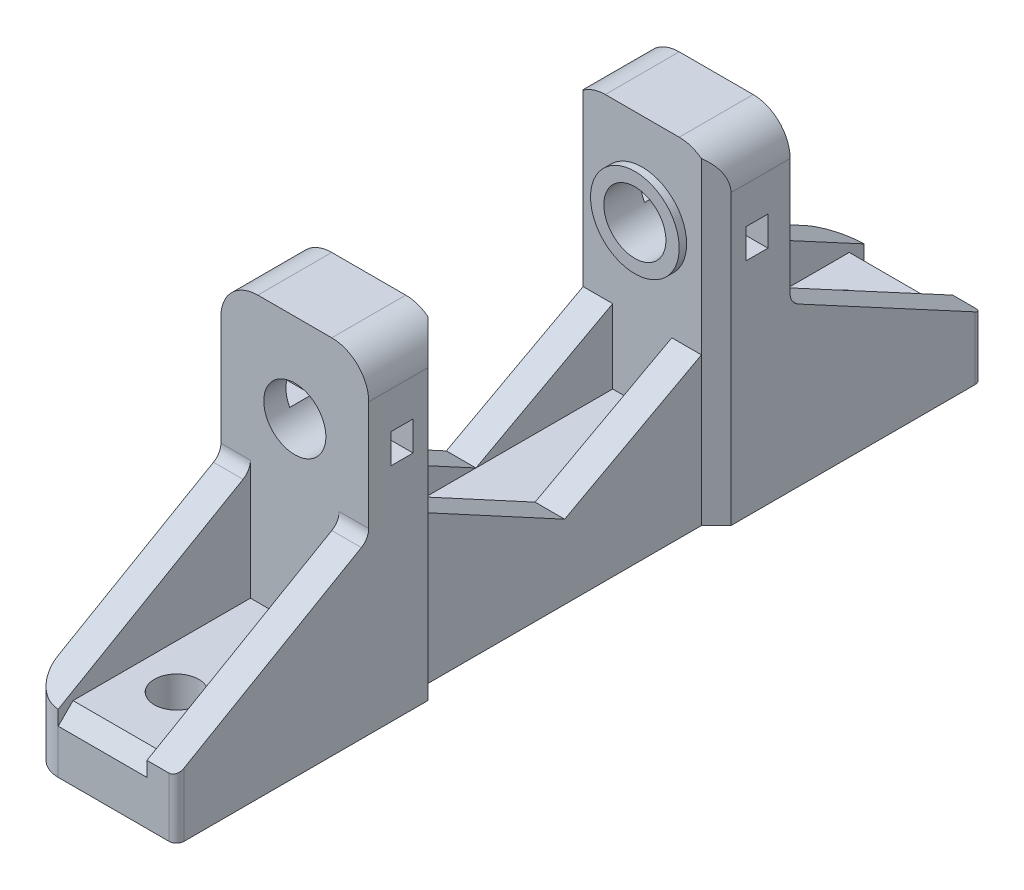
SolidWorks part; units mm, degrees
ref_plane "Спереди" through (0, 0, 0) normal (0, 0, 1) x (1, 0, 0)
ref_plane "Сверху" through (0, 0, 0) normal (0, 1, 0) x (1, 0, 0)
ref_plane "Справа" through (0, 0, 0) normal (1, 0, 0) x (0, 0, -1)
sketch "Эскиз1" plane through (0, 0, 0) normal (0, 0, 1) x (1, 0, 0)
  line L0 (-10, 0) -> (10, 0)
  line L2 (-10, 0) -> (-10, 44)
  line L3 (-10, 44) -> (10, 44)
  line L4 (10, 44) -> (10, 0)
  circle A0 centre (0, 32) radius 4.2
extrude "Бобышка-Вытянуть1" add sketch "Эскиз1" along normal blind 7
ref_plane "Плоскость1" through (0, 0, 7) normal (0, 0, 1) x (1, 0, 0)
sketch "Эскиз2" plane through (0, 0, 7) normal (0, 0, 1) x (1, 0, 0)
  line L0 (-10, 44) -> (10, 44)
  line L1 (10, 44) -> (10, 0)
  line L2 (10, 0) -> (-10, 0)
  line L3 (-10, 0) -> (-10, 44)
extrude "Бобышка-Вытянуть2" add sketch "Эскиз2" along normal blind 3
sketch "Эскиз3" plane through (0, 0, 0) normal (0, 1, 0) x (1, 0, 0)
  line L0 (-10, -10) -> (-10, -36)
  line L1 (-10, -36) -> (10, -36)
  line L2 (10, -36) -> (10, -10)
  line L3 (-10, -10) -> (10, -10)
  circle A0 centre (0, -26) radius 3
  point P6 (0, 0)
  point P7 (0, 0)
  point P8 (0, 0)
  point P11 (0, 0)
extrude "Бобышка-Вытянуть4" add sketch "Эскиз3" along normal blind 8
ref_plane "Плоскость2" through (-10, 0, 0) normal (-1, 0, 0) x (0, 0, 1)
sketch "Эскиз4" plane through (-10, 0, 0) normal (-1, 0, 0) x (0, 0, 1)
  line L0 (36, 8) -> (10, 8)
  line L1 (10, 8) -> (10, 23)
  line L2 (10, 44) -> (10, 8) construction
  line L3 (10, 23) -> (36, 8)
extrude "Бобышка-Вытянуть5" add sketch "Эскиз4" against normal blind 4
ref_plane "Плоскость3" through (10, 0, 0) normal (1, 0, 0) x (0, 0, -1)
sketch "Эскиз5" plane through (10, 0, 0) normal (1, 0, 0) x (0, 0, -1)
  line L0 (-36, 8) -> (-10, 23)
  line L1 (-10, 8) -> (-10, 44) construction
  line L2 (-36, 8) -> (-10, 23) construction
  line L3 (-10, 23) -> (-10, 8)
  line L4 (-10, 8) -> (-36, 8)
extrude "Бобышка-Вытянуть6" add sketch "Эскиз5" against normal blind 4
chamfer "Фаска1" distance 2 angle 45 2 edges at (10, 22, 0) (-10, 22, 0)
fillet "Скругление2" radius 5 2 edges at (-10, 44, 6) (10, 44, 6)
fillet "Скругление3" radius 1 1 edges at (10, 4, 36)
fillet "Скругление4" radius 2 2 edges at (8, 23, 10) (-8, 23, 10)
sketch "Эскиз6" plane through (0, 0, 0) normal (0, 1, 0) x (1, 0, 0)
  line L2 (8, 37) -> (-8, 37)
  line L3 (-8, 37) -> (-8, 0)
  line L4 (8, 37) -> (8, 0)
  line L5 (5, 0) -> (-5, 0) construction
  line L6 (8, 0) -> (-8, 0)
  point P0 (0, 0)
extrude "Бобышка-Вытянуть7" add sketch "Эскиз6" along normal blind 10
ref_plane "Плоскость4" through (0, 0, -37) normal (0, 0, -1) x (-1, 0, 0)
sketch "Эскиз7" plane through (0, 0, -37) normal (0, 0, -1) x (-1, 0, 0)
  line L0 (0, 0) -> (-10, 0)
  line L1 (-10, 21.45) -> (-10, -21.45) construction
  line L2 (-8, 0) -> (-10, 0) construction
  line L3 (-10, 0) -> (-10, 44)
  line L4 (-10, 44) -> (10, 44)
  line L5 (10, 44) -> (10, 0)
  line L6 (10, -21.45) -> (10, 21.45) construction
  line L7 (10, 0) -> (0, 0)
  circle A0 centre (0, 32) radius 4.2
extrude "Бобышка-Вытянуть8" add sketch "Эскиз7" along normal blind 7
chamfer "Фаска2" distance 2 angle 45 2 edges at (10, 22, -37) (-10, 22, -37)
ref_plane "Плоскость5" through (0, 0, -44) normal (0, 0, -1) x (-1, 0, 0)
sketch "Эскиз8" plane through (0, 0, -44) normal (0, 0, -1) x (-1, 0, 0)
  line L0 (-10, 0) -> (10, 0)
  line L1 (-10, 0) -> (10, 0) construction
  line L2 (-10, 21.45) -> (-10, -21.45) construction
  line L3 (10, 0) -> (10, 44)
  line L4 (10, 44) -> (-10, 44)
  line L5 (-10, 44) -> (-10, 0)
extrude "Бобышка-Вытянуть9" add sketch "Эскиз8" along normal blind 3
sketch "Эскиз9" plane through (0, 0, 0) normal (0, 1, 0) x (1, 0, 0)
  line L0 (-10, 47) -> (-10, 73)
  line L1 (-10, 73) -> (10, 73)
  line L2 (10, 73) -> (10, 47)
  line L3 (10, 47) -> (-10, 47)
  circle A0 centre (0, 64) radius 3
  point P3 (0, 0)
  point P7 (0, 0)
  point P10 (0, 0)
extrude "Бобышка-Вытянуть10" add sketch "Эскиз9" along normal blind 8
sketch "Эскиз10" plane through (-10, 0, 0) normal (-1, 0, 0) x (0, 0, 1)
  line L0 (-73, 8) -> (-47, 8)
  line L1 (-47, 8) -> (-47, 22)
  line L2 (-47, 8) -> (-47, 44) construction
  line L3 (-47, 22) -> (-73, 8)
extrude "Бобышка-Вытянуть11" add sketch "Эскиз10" against normal blind 4
sketch "Эскиз11" plane through (10, 0, 0) normal (1, 0, 0) x (0, 0, -1)
  line L0 (47, 8) -> (47, 22)
  line L1 (47, 22) -> (73, 8)
  line L2 (73, 8) -> (47, 8)
extrude "Бобышка-Вытянуть12" add sketch "Эскиз11" against normal blind 4
fillet "Скругление5" radius 2 2 edges at (8, 22, -47) (-8, 22, -47)
fillet "Скругление7" radius 1 1 edges at (10, 4, -73)
fillet "Скругление8" radius 5 2 edges at (-10, 44, -43) (10, 44, -43)
sketch "Эскиз12" plane through (10, 0, 0) normal (1, 0, 0) x (0, 0, -1)
  line L0 (-7, 30) -> (-7, 34)
  line L3 (-7, 55) -> (-7, -55) construction
  line L5 (-7, 34) -> (-4, 34)
  line L6 (-4, 34) -> (-4, 30)
  line L7 (-4, 30) -> (-7, 30)
  line L9 (41, 30) -> (41, 34)
  line L10 (41, 34) -> (44, 34)
  line L11 (44, -55) -> (44, 55) construction
  line L12 (44, 34) -> (44, 30)
  line L13 (44, 30) -> (41, 30)
extrude "Вырез-Вытянуть1" cut sketch "Эскиз12" against normal through all
ref_plane "Плоскость6" through (8, 0, 0) normal (1, 0, 0) x (0, 0, -1)
sketch "Эскиз13" plane through (8, 0, 0) normal (1, 0, 0) x (0, 0, -1)
  line L0 (0, 10) -> (0, 20)
  line L1 (0, 43) -> (0, 10) construction
  line L2 (0, 10) -> (18.5, 10)
  line L3 (0, 10) -> (37, 10) construction
  line L4 (18.5, 10) -> (0, 20)
  line L5 (18.5, 10) -> (37, 10)
  line L6 (37, -25.6899) -> (37, 25.6899) construction
  line L7 (37, 10) -> (37, 20)
  line L8 (37, 20) -> (18.5, 10)
extrude "Бобышка-Вытянуть13" add sketch "Эскиз13" against normal blind 4 contours L2 L4 L0 | L7 L8 L5
ref_plane "Плоскость7" through (-8, 0, 0) normal (-1, 0, 0) x (0, 0, 1)
sketch "Эскиз14" plane through (-8, 0, 0) normal (-1, 0, 0) x (0, 0, 1)
  line L0 (-37, 10) -> (-37, 20)
  line L1 (-37, 25.6899) -> (-37, -25.6899) construction
  line L2 (-37, 20) -> (-18.5, 10)
  line L3 (-37, 10) -> (0, 10) construction
  line L4 (-18.5, 10) -> (0, 20)
  line L5 (0, 10) -> (0, 43) construction
  line L6 (-18.5, 10) -> (0, 20) construction
  line L7 (0, 20) -> (0, 10)
  line L8 (-37, 10) -> (-18.5, 10)
  line L9 (0, 10) -> (-18.5, 10)
extrude "Бобышка-Вытянуть14" add sketch "Эскиз14" against normal blind 4 contours L9 L7 L4 | L0 L8 L2
sketch "Эскиз15" plane through (0, 0, -37) normal (0, 0, -1) x (-1, 0, 0)
  circle A0 centre (0, 32) radius 4.2
extrude "Вырез-Вытянуть2" cut sketch "Эскиз15" against normal through all both and the other way through all
sketch "Эскиз16" plane through (0, 0, -37) normal (0, 0, -1) x (-1, 0, 0)
  circle A0 centre (0, 32) radius 4.2
  circle A1 centre (0, 32) radius 6
extrude "Бобышка-Вытянуть15" add sketch "Эскиз16" against normal blind 1
ref_plane "Плоскость12" through (0, 0, 0) normal (0, 0, -1) x (-1, 0, 0)
sketch "Эскиз17" plane through (0, 0, 0) normal (0, 0, -1) x (-1, 0, 0)
  circle A0 centre (0, 32) radius 4.2
  circle A1 centre (0, 32) radius 6
extrude "Бобышка-Вытянуть16" add sketch "Эскиз17" along normal blind 1
chamfer "Фаска3" distance 2 angle 45 2 edges at (0, 8, 36) (0, 8, -73)
fillet "Скругление9" radius 4 2 edges at (-10, 4, 36) (-10, 4, -73)
